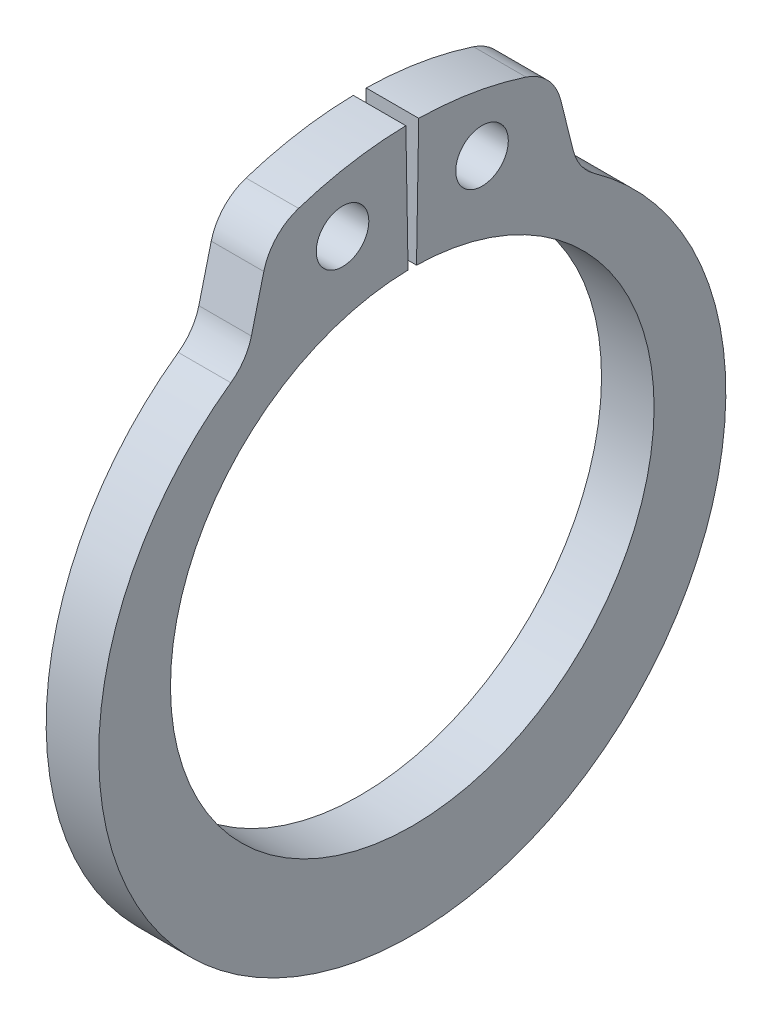
SolidWorks part; units mm, degrees
material "Cast Carbon Steel"
ref_plane "Front" through (0, 0, 0) normal (0, 0, 1) x (1, 0, 0)
ref_plane "Top" through (0, 0, 0) normal (0, 1, 0) x (1, 0, 0)
ref_plane "Right" through (0, 0, 0) normal (1, 0, 0) x (0, 0, -1)
sketch "Sketch1" plane through (0, 0, 0) normal (1, 0, 0) x (0, 0, -1)
  line L0 (0, 0) -> (0, 5.842) construction
  line L1 (-0.102, 5.8411) -> (-0.1552, 8.8886)
  line L2 (-0.1552, 8.8886) -> (-3.268, 8.8343) construction
  line L3 (-3.268, 8.8343) -> (-4.0054, 5.8768) construction
  line L4 (0.1552, 8.8886) -> (0.102, 5.8411)
  line L5 (0.1552, 8.8886) -> (3.268, 8.8343) construction
  line L6 (3.268, 8.8343) -> (4.0054, 5.8768) construction
  line L7 (-4.0054, 5.8768) -> (-3.2901, 4.8274) construction
  line L8 (4.0054, 5.8768) -> (3.2901, 4.8274) construction
  line L9 (0, -5.842) -> (0, -8.128) construction
  line L10 (-3.268, 8.8343) -> (-0.102, 5.8411) construction
  line L11 (-5.842, 0) -> (5.842, 0) construction
  line L12 (0, 5.842) -> (0, 8.89) construction
  line L13 (3.4253, 8.2036) -> (4.0054, 5.8768)
  line L14 (-3.4253, 8.2036) -> (-4.0054, 5.8768)
  circle A0 centre (0, 0) radius 5.842 construction
  arc A1 (-0.102, 5.8411) -> (0.102, 5.8411) centre (0, 0) ccw
  circle A2 centre (0, -0.5528) radius 7.5752 construction
  circle A3 centre (0, 0) radius 8.89 construction
  circle A4 centre (-1.685, 7.3377) radius 0.635
  circle A5 centre (1.685, 7.3377) radius 0.635
  arc A6 (-4.0054, 5.8768) -> (4.0054, 5.8768) centre (0, -0.5528) ccw
  arc A7 (0.1552, 8.8886) -> (3.4253, 8.2036) centre (0, 0) cw
  arc A8 (-0.1552, 8.8886) -> (-3.4253, 8.2036) centre (0, 0) ccw
  dimension "D1" = 75
  dimension "A" = 11.684
  dimension "L" = 17.78
  dimension "Hole" = 1.27
  dimension "Smin" = 1.27
  dimension "Smax" = 2.286
  dimension "H" = 3.048
  dimension "Angle" = 1
extrude "Extrude1" add sketch "Sketch1" along normal mid plane 1.27
fillet "Fillet1" radius 1.27 4 edges at (0, 5.8768, 4.0054) (0, 8.2036, 3.4253) (0, 8.2036, -3.4253) (0, 5.8768, -4.0054)
sketch "Sketch2" plane through (0, 0, 0) normal (0, 0, 1) x (1, 0, 0)
  line L0 (-3.556, 0) -> (10.668, 0)
  line L1 (10.668, 0) -> (10.668, -6.35)
  line L3 (10.668, -6.35) -> (0.7112, -6.35)
  line L4 (0.7112, -6.35) -> (0.7112, -5.9436)
  line L5 (0.7112, -5.9436) -> (-0.7112, -5.9436)
  line L6 (-0.7112, -5.9436) -> (-0.7112, -6.35)
  line L7 (-0.7112, -6.35) -> (-3.556, -6.35) construction
  line L8 (-3.556, -6.35) -> (-3.556, 0) construction
  line L9 (0, -5.9436) -> (0, 0) construction
  line L10 (10.668, 0) -> (14.0551, 0) construction
  line L11 (-0.7112, -6.35) -> (-3.3528, -6.35)
  line L12 (-3.3528, -6.35) -> (-3.556, -6.1468)
  line L13 (-3.556, -6.1468) -> (-3.556, 0)
  point P14 (-0.7112, -6.1468)
  dimension "Dg" = 11.8872
  dimension "Ds" = 12.7
  dimension "D2" = 14.224
  dimension "W" = 1.4224
  dimension "D3" = 3.556
  dimension "D4" = 45
revolve "Revolve1" [suppressed] add sketch "Sketch2" angle 360 about L10
equation "\"D2@Sketch2\" = \"W@Sketch2\"*10"
equation "\"D3@Sketch2\" = \"D2@Sketch2\"/4"
